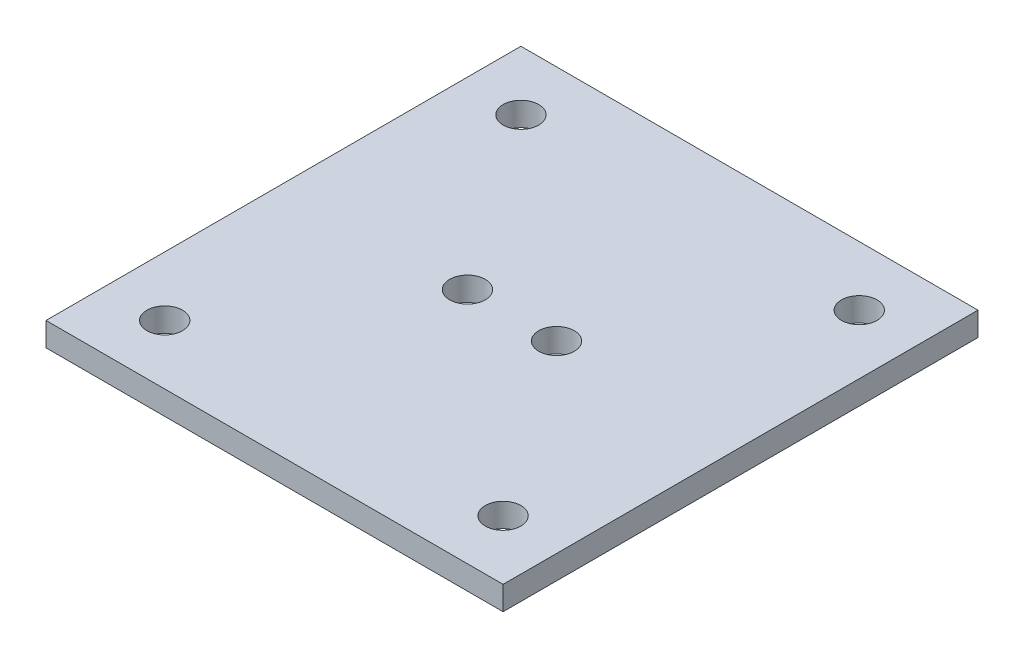
SolidWorks part; units mm, degrees
ref_plane "Front Plane" through (0, 0, 0) normal (0, 0, 1) x (1, 0, 0)
ref_plane "Top Plane" through (0, 0, 0) normal (0, 1, 0) x (1, 0, 0)
ref_plane "Right Plane" through (0, 0, 0) normal (1, 0, 0) x (0, 0, -1)
sketch "Sketch1" plane through (0, 0, 0) normal (0, 1, 0) x (1, 0, 0)
  line L0 (-1000, 0) -> (49000, 0) construction
  line L1 (38.5, -40) -> (-38.5, -40)
  line L2 (38.5, -40) -> (38.5, 40)
  line L3 (38.5, 40) -> (-38.5, 40)
  line L4 (-38.5, -40) -> (-38.5, 40)
  line L5 (38.5, -40) -> (-38.5, 40) construction
  line L6 (38.5, 40) -> (-38.5, -40) construction
  circle A0 centre (-7.5, 0) radius 3
  circle A1 centre (7.5, 0) radius 3
  circle A2 centre (-28.5, 30) radius 3
  circle A3 centre (28.5, 30) radius 3
  circle A4 centre (28.5, -30) radius 3
  circle A5 centre (-28.5, -30) radius 3
  point P0 (0, 0)
  dimension "D3" = 7.5
  dimension "D4" = 6
  dimension "D5" = 7.5
  dimension "D6" = 6
  dimension "D7" = 6
  dimension "D8" = 6
  dimension "D9" = 10
  dimension "D10" = 10
  dimension "D11" = 10
  dimension "D12" = 10
  dimension "D1" = 77
  dimension "D2" = 80
extrude "Boss-Extrude1" add sketch "Sketch1" along normal mid plane 4
